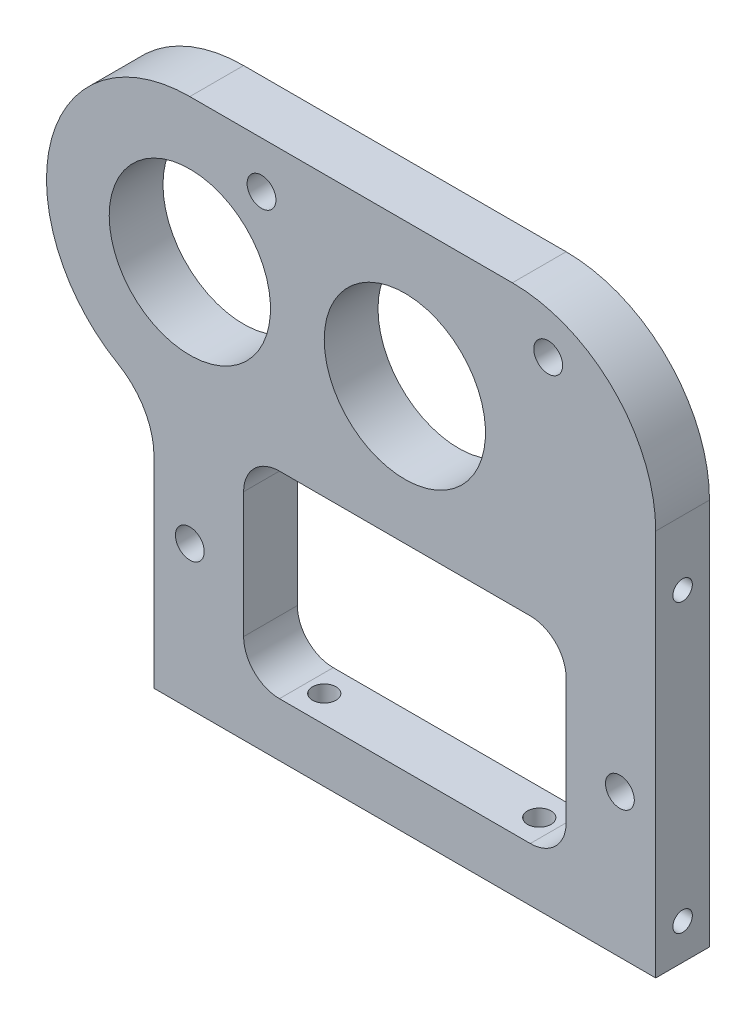
SolidWorks part; units mm, degrees
ref_plane "Front Plane" through (0, 0, 0) normal (0, 0, 1) x (1, 0, 0)
ref_plane "Top Plane" through (0, 0, 0) normal (0, 1, 0) x (1, 0, 0)
ref_plane "Right Plane" through (0, 0, 0) normal (1, 0, 0) x (0, 0, -1)
sketch "Sketch1" plane through (0, 0, 0) normal (0, 0, 1) x (1, 0, 0)
  line L0 (0, 68.58) -> (0, 92.1289) construction
  line L1 (-44.45, 35.5844) -> (-44.45, 0)
  line L3 (-44.45, 0) -> (44.45, 0)
  line L4 (44.45, 68.58) -> (44.45, 0)
  line L8 (-38.1, 93.98) -> (19.05, 93.98)
  circle A0 centre (0, 68.58) radius 14.2875
  circle A1 centre (-38.1, 68.58) radius 14.2875
  arc A2 (-38.1, 93.98) -> (-50.8, 46.583) centre (-38.1, 68.58) ccw
  arc A3 (19.05, 93.98) -> (44.45, 68.58) centre (19.05, 68.58) cw
  arc A4 (-50.8, 46.583) -> (-44.45, 35.5844) centre (-57.15, 35.5844) cw
  dimension "D1" = 28.575
  dimension "D5" = 28.575
  dimension "D6" = 25.4
  dimension "D3" = 50.8
  dimension "D7" = 12.7
  dimension "D2" = 68.58
  dimension "D4" = 88.9
  dimension "D8" = 38.1
extrude "Boss-Extrude1" add sketch "Sketch1" along normal mid plane 9.525
hole_wizard "#8-32 Tapped Hole1" positions "Sketch4" profile "Sketch3" tap size "#8-32" standard "Ansi Inch"
sketch "Sketch4" plane through (0, 0, 0) normal (0, -1, 0) x (1, 0, 0)
  line L0 (0, 0) -> (0, 11.6747) construction
  point P0 (-19.05, 0)
  point P1 (19.05, 0)
  dimension "D1" = 38.1
sketch "Sketch3" plane through (-19.05, 0, 0) normal (1, 0, 0) x (0, 0, -1)
  line L0 (0, 0) -> (0, 20.0878)
  line L1 (0, 20.0878) -> (1.7272, 19.05)
  line L2 (1.7272, 19.05) -> (1.7272, 15.875)
  line L3 (1.7272, 15.875) -> (2.0828, 15.875)
  line L4 (2.0828, 15.875) -> (2.0828, 0)
  line L5 (2.0828, 0) -> (0, 0)
  line L10 (0, 20.0878) -> (-1.7272, 19.05) construction
  line L11 (0, -6.35) -> (0, 107.95) construction
  dimension "Tap Drill Dia." = 3.4544
  dimension "Tap Drill Depth" = 19.05
  dimension "Thread Major Dia." = 4.1656
  dimension "Thread Depth" = 15.875
  dimension "Drill Angle" = 118
hole_wizard "#8-32 Tapped Hole2" positions "Sketch6" profile "Sketch5" tap size "#8-32" standard "Ansi Inch"
sketch "Sketch6" plane through (-44.45, 3.9338, -1.6969) normal (-1, 0, 0) x (0, 0, 1)
  point P0 (1.6969, 15.1162)
  point P1 (1.6969, 2.4162)
  dimension "D1" = 6.35
  dimension "D2" = 12.7
sketch "Sketch5" plane through (-44.45, 19.05, 0) normal (0, 1, 0) x (0, 0, 1)
  line L0 (0, 0) -> (0, 13.3314)
  line L1 (0, 13.3314) -> (1.7272, 12.2936)
  line L2 (1.7272, 12.2936) -> (1.7272, 0)
  line L5 (1.7272, 0) -> (0, 0)
  line L10 (0, 13.3314) -> (-1.7272, 12.2936) construction
  line L11 (0, -6.35) -> (0, 107.95) construction
  dimension "Tap Drill Dia." = 3.4544
  dimension "Tap Drill Depth" = 12.2936
  dimension "Drill Angle" = 118
sketch "Sketch7" plane through (0, 0, 4.7625) normal (0, 0, 1) x (1, 0, 0)
  line L0 (0, 0) -> (0, 9.525) construction
  line L1 (-22.225, 44.45) -> (22.225, 44.45)
  line L2 (-28.575, 38.1) -> (-28.575, 15.875)
  line L3 (-22.225, 9.525) -> (22.225, 9.525)
  line L4 (28.575, 38.1) -> (28.575, 15.875)
  line L5 (-44.45, 0) -> (44.45, 0) construction
  arc A0 (22.225, 9.525) -> (28.575, 15.875) centre (22.225, 15.875) ccw
  arc A1 (-28.575, 15.875) -> (-22.225, 9.525) centre (-22.225, 15.875) ccw
  arc A2 (-22.225, 44.45) -> (-28.575, 38.1) centre (-22.225, 38.1) ccw
  arc A3 (22.225, 44.45) -> (28.575, 38.1) centre (22.225, 38.1) cw
  point P13 (-28.575, 9.525)
  point P16 (-28.575, 44.45)
  point P19 (28.575, 44.45)
  dimension "D4" = 6.35
  dimension "D1" = 34.925
  dimension "D2" = 57.15
  dimension "D3" = 9.525
extrude "Cut-Extrude2" cut sketch "Sketch7" against normal through all
hole_wizard "#8-32 Tapped Hole3" positions "Sketch9" profile "Sketch8" tap size "#8-32" standard "Ansi Inch"
sketch "Sketch9" plane through (44.45, 0, 0) normal (1, 0, 0) x (0, 0, -1)
  line L0 (-4.7625, 0) -> (4.7625, 0) construction
  point P0 (0, 6.35)
  point P1 (0, 57.15)
  dimension "D1" = 6.35
  dimension "D2" = 57.15
sketch "Sketch8" plane through (44.45, 6.35, 0) normal (0, 1, 0) x (0, 0, -1)
  line L0 (0, 0) -> (0, 13.3314)
  line L1 (0, 13.3314) -> (1.7272, 12.2936)
  line L2 (1.7272, 12.2936) -> (1.7272, 0)
  line L5 (1.7272, 0) -> (0, 0)
  line L10 (0, 13.3314) -> (-1.7272, 12.2936) construction
  line L11 (0, -6.35) -> (0, 107.95) construction
  dimension "Tap Drill Dia." = 3.4544
  dimension "Tap Drill Depth" = 12.2936
  dimension "Drill Angle" = 118
hole_wizard "#10 Clearance Hole1" positions "Sketch11" profile "Sketch10" hole size "#10" standard "Ansi Inch"
sketch "Sketch11" plane through (0, 0, -4.7625) normal (0, 0, -1) x (-1, 0, 0)
  line L0 (0, 0) -> (0, 40.284) construction
  line L1 (44.45, 0) -> (-44.45, 0) construction
  point P0 (-25.4, 85.725)
  point P1 (25.4, 85.725)
  point P3 (38.1, 25.4)
  point P5 (-38.1, 25.4)
  dimension "D1" = 76.2
  dimension "D2" = 25.4
  dimension "D3" = 60.325
  dimension "D4" = 50.8
sketch "Sketch10" plane through (25.4, 85.725, -4.7625) normal (1, 0, 0) x (0, 1, 0)
  line L0 (0, 0) -> (0, 11.0588)
  line L1 (0, 11.0588) -> (2.5527, 9.525)
  line L2 (2.5527, 9.525) -> (2.5527, 0)
  line L5 (2.5527, 0) -> (0, 0)
  line L10 (0, 11.0588) -> (-2.5527, 9.525) construction
  line L11 (0, -6.35) -> (0, 107.95) construction
  dimension "Hole Dia." = 5.1054
  dimension "Hole Depth" = 9.525
  dimension "Drill Angle" = 118
